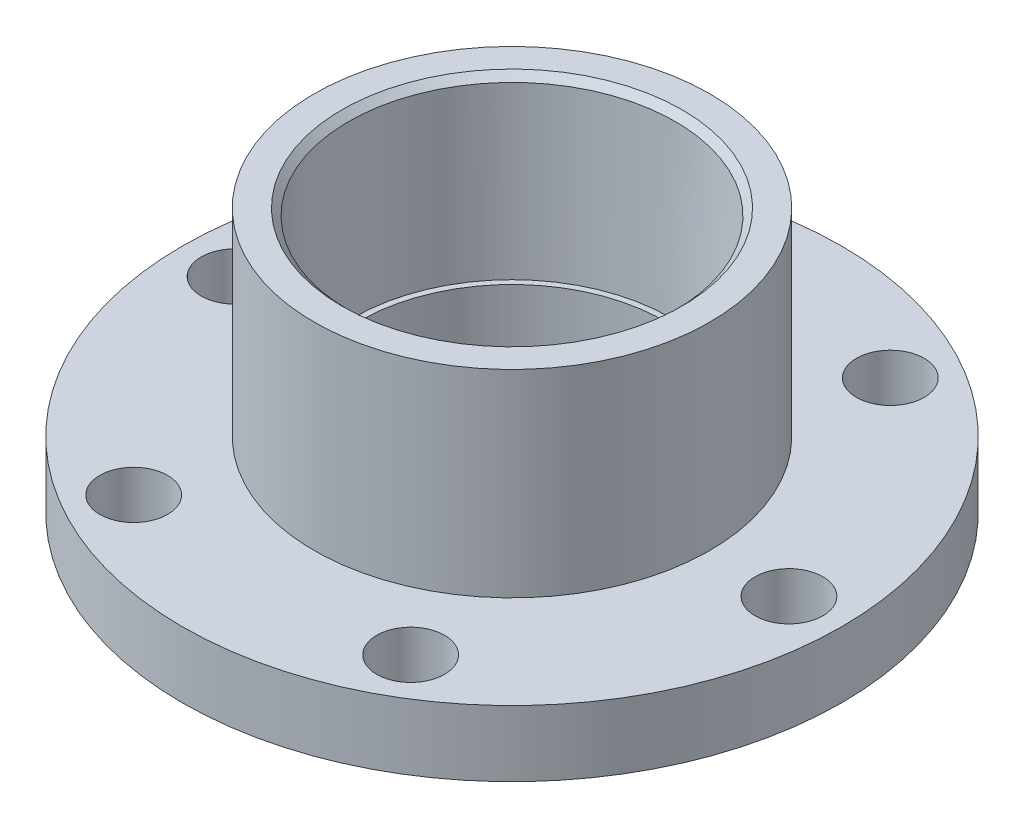
SolidWorks part; units mm, degrees
material "6061-T6 (SS)"
ref_plane "Front Plane" through (0, 0, 0) normal (0, 0, 1) x (1, 0, 0)
ref_plane "Top Plane" through (0, 0, 0) normal (0, 1, 0) x (1, 0, 0)
ref_plane "Right Plane" through (0, 0, 0) normal (1, 0, 0) x (0, 0, -1)
sketch "Sketch4" plane through (0, 0, 0) normal (0, 0, 1) x (1, 0, 0)
  line L0 (0, 0) -> (0, 22.0854) construction
  line L1 (0, 25.4) -> (19.05, 25.4)
  line L2 (19.05, 25.4) -> (19.05, 6.35)
  line L3 (19.05, 6.35) -> (31.75, 6.35)
  line L4 (31.75, 6.35) -> (31.75, 0)
  line L5 (31.75, 0) -> (21.5773, 0)
  line L6 (0, 25.4) -> (0, 0)
  line L7 (16.9545, 0) -> (16.9545, 2.2606)
  line L8 (17.3355, 2.6416) -> (21.1963, 2.6416)
  line L9 (21.5773, 2.2606) -> (21.5773, 0)
  line L10 (16.9545, 0) -> (0, 0)
  arc A0 (21.5773, 2.2606) -> (21.1963, 2.6416) centre (21.1963, 2.2606) ccw
  arc A1 (16.9545, 2.2606) -> (17.3355, 2.6416) centre (17.3355, 2.2606) cw
  point P16 (21.5773, 2.6416)
  dimension "D8" = 0.381
  dimension "D1" = 38.1
  dimension "D2" = 63.5
  dimension "D3" = 6.35
  dimension "D4" = 19.05
  dimension "D5" = 4.6228
  dimension "D6" = 43.1546
  dimension "D7" = 2.6416
revolve "Revolve1" add sketch "Sketch4" angle 360 about L0
hole_wizard "1 NPT Tapped Hole2" positions "Sketch5" profile "Sketch6" size "1" standard "ANSI Inch" end condition through all
sketch "Sketch5" plane through (0, 25.4, 0) normal (0, 1, 0) x (1, 0, 0)
  point P0 (0, 0)
sketch "Sketch6" plane through (0, 25.4, 0) normal (1, 0, 0) x (0, 0, 1)
  line L0 (0, 0) -> (0, 25.4)
  line L1 (0, 25.4) -> (14.6844, 25.4)
  line L3 (14.6844, 25.4) -> (14.6844, 16.764)
  line L4 (14.6844, 16.764) -> (15.2475, 16.764)
  line L5 (15.2475, 16.764) -> (15.7299, 0.6531)
  line L6 (15.7299, 0.6531) -> (16.383, 0)
  line L7 (16.383, 0) -> (0, 0)
  line L8 (0, -6.35) -> (0, 107.95) construction
  line L9 (-15.7299, 0.6531) -> (-16.383, 0) construction
  line L11 (-14.6844, 16.764) -> (-15.2475, 16.764) construction
  line L12 (-15.2475, 16.764) -> (-15.7299, 0.6531) construction
  dimension "Thru Tap Drill Dia." = 29.3687
  dimension "Thru Tap Drill Depth" = 25.4
  dimension "Thread Dia." = 31.4598
  dimension "Thread Angle" = 3.43
  dimension "Thread Depth" = 16.764
  dimension "Near C'Sink Dia." = 32.766
  dimension "Near C'Sink Angle" = 90
cosmetic thread "Hole Thread2" parameters "D1"=16.764, "D2"=33.3988
sketch "Sketch7" plane through (0, 6.35, 0) normal (0, 1, 0) x (1, 0, 0)
  circle A0 centre (0, 0) radius 26.67 construction
  point P3 (26.67, 0)
  dimension "D1" = 53.34
hole_wizard "1/4 Clearance Hole1" positions "Sketch8" profile "Sketch10" hole size "1/4" standard "ANSI Inch" end condition through all
sketch "Sketch8" plane through (0, 6.35, 0) normal (0, 1, 0) x (1, 0, 0)
  point P0 (26.67, 0)
sketch "Sketch10" plane through (26.67, 6.35, 0) normal (1, 0, 0) x (0, 0, 1)
  line L0 (0, 0) -> (0, 6.35)
  line L1 (0, 6.35) -> (3.2639, 6.35)
  line L2 (3.2639, 6.35) -> (3.2639, 0)
  line L5 (3.2639, 0) -> (0, 0)
  line L11 (0, -6.35) -> (0, 107.95) construction
  dimension "Thru Hole Dia." = 6.5278
  dimension "Thru Hole Depth" = 6.35
pattern_circular "CirPattern1" count 6 over 360 about axis through (0, 0, 0) along (0, 1, 0) of "1/4 Clearance Hole1"
